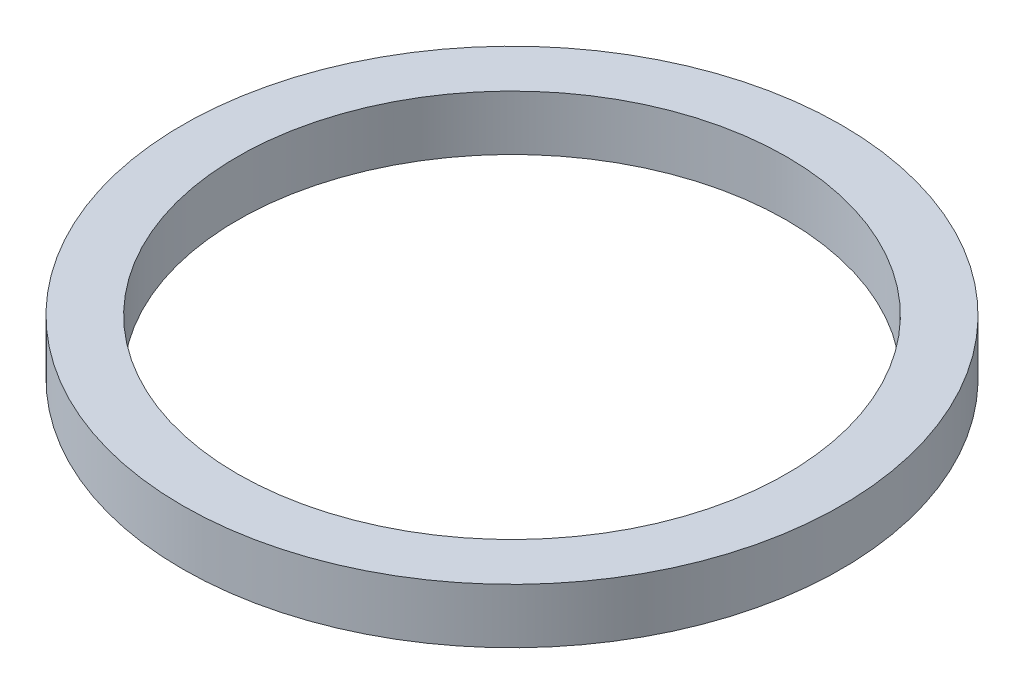
SolidWorks part; units mm, degrees
ref_plane "Front Plane" through (0, 0, 0) normal (0, 0, 1) x (1, 0, 0)
ref_plane "Top Plane" through (0, 0, 0) normal (0, 1, 0) x (1, 0, 0)
ref_plane "Right Plane" through (0, 0, 0) normal (1, 0, 0) x (0, 0, -1)
sketch "Sketch1" plane through (0, 0, 0) normal (0, 1, 0) x (1, 0, 0)
  circle A0 centre (0, 0) radius 6
  circle A1 centre (0, 0) radius 5
  dimension "D1" = 12
  dimension "D2" = 10
extrude "Boss-Extrude1" add sketch "Sketch1" along normal blind 1
